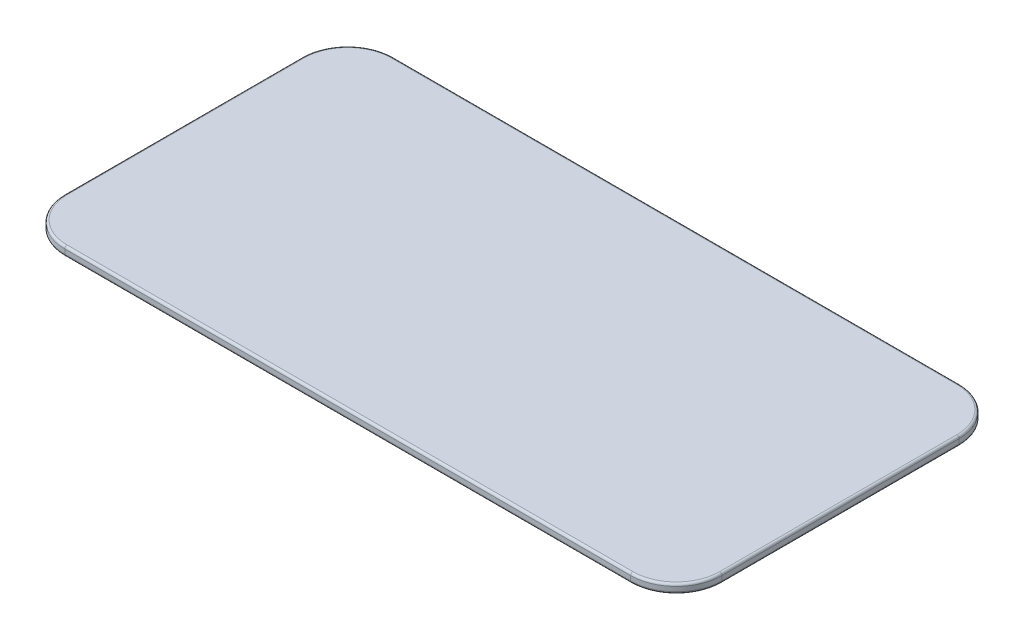
SolidWorks part; units mm, degrees
ref_plane "Front Plane" through (0, 0, 0) normal (0, 0, 1) x (1, 0, 0)
ref_plane "Top Plane" through (0, 0, 0) normal (0, 1, 0) x (1, 0, 0)
ref_plane "Right Plane" through (0, 0, 0) normal (1, 0, 0) x (0, 0, -1)
sketch "Sketch1" plane through (0, 0, 0) normal (0, 1, 0) x (1, 0, 0)
  line L1 (-914.4, -457.2) -> (914.4, -457.2)
  line L2 (-914.4, -457.2) -> (-914.4, 457.2)
  line L3 (-914.4, 457.2) -> (914.4, 457.2)
  line L4 (914.4, -457.2) -> (914.4, 457.2)
  line L5 (-914.4, -457.2) -> (914.4, 457.2) construction
  line L6 (-914.4, 457.2) -> (914.4, -457.2) construction
  point P0 (0, 0)
  dimension "D1" = 1828.8
  dimension "D2" = 914.4
extrude "Boss-Extrude1" add sketch "Sketch1" along normal blind 25.4
fillet "Fillet1" radius 127 4 edges at (-914.4, 12.7, -457.2) (-914.4, 12.7, 457.2) (914.4, 12.7, -457.2) (914.4, 12.7, 457.2)
fillet "Fillet2" radius 6.35 16 edges at (-877.2026, 0, 420.0026) (0, 0, 457.2) (877.2026, 0, 420.0026) (914.4, 0, 0) (877.2026, 0, -420.0026) (0, 0, -457.2) (-877.2026, 0, -420.0026) (-914.4, 0, 0) (877.2026, 25.4, -420.0026) (914.4, 25.4, 0) (877.2026, 25.4, 420.0026) (0, 25.4, 457.2) (-877.2026, 25.4, 420.0026) (-914.4, 25.4, 0) (-877.2026, 25.4, -420.0026) (0, 25.4, -457.2)
